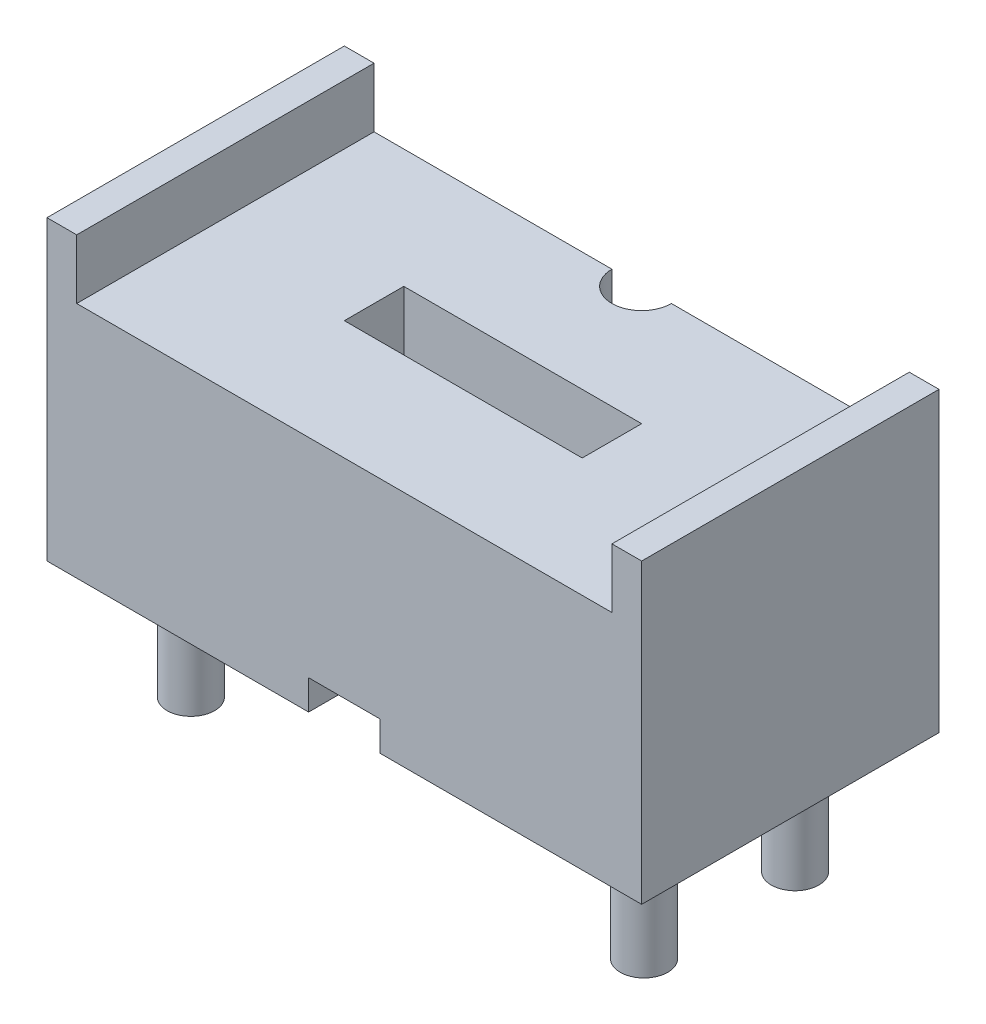
SolidWorks part; units mm, degrees
ref_plane "前视基准面" through (0, 0, 0) normal (0, 0, 1) x (1, 0, 0)
ref_plane "上视基准面" through (0, 0, 0) normal (0, 1, 0) x (1, 0, 0)
ref_plane "右视基准面" through (0, 0, 0) normal (1, 0, 0) x (0, 0, -1)
sketch "草图1" plane through (0, 0, 0) normal (0, 1, 0) x (1, 0, 0)
  line L0 (0, 0) -> (10, 0)
  line L1 (10, 0) -> (10, 5)
  line L2 (10, 5) -> (0, 5)
  line L3 (0, 5) -> (0, 0)
  dimension "D1" = 10
  dimension "D2" = 5
extrude "凸台-拉伸1" add sketch "草图1" along normal blind 5
sketch "草图2" plane through (0, 5, 0) normal (0, 1, 0) x (-1, 0, 0)
  line L0 (-5, -5) -> (-5, 0) construction
  line L1 (-10, -5) -> (0, -5) construction
  line L2 (0, 0) -> (-10, 0) construction
  circle A0 centre (-5, -5) radius 0.5
  dimension "D1" = 1
extrude "切除-拉伸1" cut sketch "草图2" against normal up to next
sketch "草图4" plane through (0, 0, 0) normal (0, 0, 1) x (1, 0, 0)
  line L0 (5, 5) -> (5, 0) construction
  line L1 (0, 5) -> (10, 5) construction
  line L2 (0, 0) -> (10, 0) construction
  line L3 (5.6, 0.5) -> (5.6, 0)
  line L4 (4.4, 0.5) -> (4.4, 0)
  line L5 (4.4, 0.5) -> (5.6, 0.5)
  line L6 (0.5, 5) -> (0.5, 4)
  line L7 (0.5, 4) -> (9.5, 4)
  line L8 (9.5, 4) -> (9.5, 5)
  line L9 (9.5, 5) -> (0.5, 5)
  line L10 (0, 5) -> (0, 0) construction
  line L11 (10, 5) -> (10, 0) construction
  line M1 (0, 0) -> (10, 0)
  line M3 (10, 5) -> (0, 5)
  dimension "D1" = 1.2
  dimension "D2" = 0.5
  dimension "D3" = 0.5
  dimension "D4" = 0.5
  dimension "D5" = 1
extrude "切除-拉伸2" cut sketch "草图4" against normal up to next contours L0 L9 L6 L7 | L0 L7 L8 M3 | L0 L5 L4 M1 | L5 L0 L3 M1
sketch "草图5" plane through (0, 4, 0) normal (0, 1, 0) x (1, 0, 0)
  line L0 (5, 4.5) -> (5, 0) construction
  line L1 (0.5, 0) -> (9.5, 0) construction
  line L2 (3, 3) -> (3, 2)
  line L3 (3, 2) -> (7, 2)
  line L4 (7, 2) -> (7, 3)
  line L5 (7, 3) -> (3, 3)
  line L6 (0, 5) -> (0, 0) construction
  line L7 (10, 0) -> (10, 5) construction
  line L8 (4.5, 5) -> (0.5, 5) construction
  arc A0 (4.5, 5) -> (5.5, 5) centre (5, 5) ccw construction
  dimension "D1" = 3
  dimension "D2" = 3
  dimension "D3" = 2
  dimension "D4" = 2
extrude "切除-拉伸3" cut sketch "草图5" against normal up to next
sketch "草图6" plane through (0, 0, 0) normal (0, -1, 0) x (1, 0, 0)
  line L0 (5, 0) -> (5, -4.5) construction
  line L1 (4.4, 0) -> (5.6, 0) construction
  line L2 (0, -2.5) -> (10, -2.5) construction
  line L3 (0, -5) -> (0, 0) construction
  line L4 (10, 0) -> (10, -5) construction
  arc A0 (5.5, -5) -> (4.5, -5) centre (5, -5) ccw construction
  circle A1 centre (1.19, -1.23) radius 0.4
  circle A2 centre (1.19, -3.77) radius 0.4
  circle A3 centre (8.81, -3.77) radius 0.4
  circle A4 centre (8.81, -1.23) radius 0.4
  dimension "D1" = 0.8
  dimension "D2" = 1.27
  dimension "D3" = 7.62
extrude "凸台-拉伸2" add sketch "草图6" along normal blind 2
